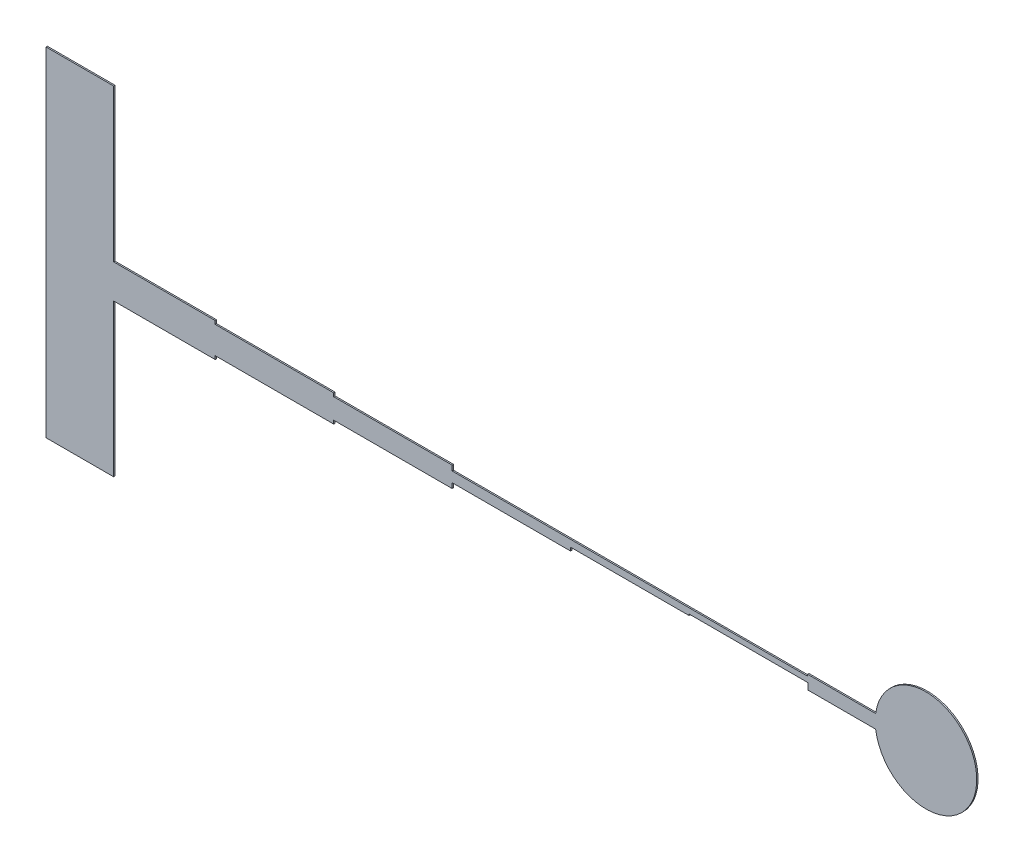
SolidWorks part; units mm, degrees
ref_plane "Front Plane" through (0, 0, 0) normal (0, 0, 1) x (1, 0, 0)
ref_plane "Top Plane" through (0, 0, 0) normal (0, 1, 0) x (1, 0, 0)
ref_plane "Right Plane" through (0, 0, 0) normal (1, 0, 0) x (0, 0, -1)
sketch "Sketch1" plane through (0, 0, 0) normal (0, 0, 1) x (1, 0, 0)
  line L0 (1000, 250) -> (5000, 250)
  line L1 (-1000, 2500) -> (1000, 2500)
  line L2 (-1000, 2500) -> (-1000, -2500)
  line L3 (-1000, -2500) -> (1000, -2500)
  line L4 (1000, 2500) -> (1000, 250)
  line L5 (-1000, 2500) -> (1000, -2500) construction
  line L6 (-1000, -2500) -> (1000, 2500) construction
  line L9 (1000, -250) -> (5000, -250)
  line L10 (5000, 250) -> (5000, 125)
  line L11 (-3000, 250) -> (5000, -250) construction
  line L12 (-3000, -250) -> (5000, 250) construction
  line L13 (5000, 125) -> (9000, 125)
  line L15 (5000, -125) -> (9000, -125)
  line L16 (9000, 125) -> (9000, 100)
  line L17 (1000, 125) -> (9000, -125) construction
  line L18 (1000, -125) -> (9000, 125) construction
  line L19 (9000, 100) -> (11256.6966, 100)
  line L21 (9000, -100) -> (11256.6966, -100)
  line L23 (6000, 100) -> (12000, -100) construction
  line L24 (6000, -100) -> (12000, 100) construction
  line L25 (1000, -250) -> (1000, -2500)
  line L26 (5000, -125) -> (5000, -250)
  line L27 (9000, -100) -> (9000, -125)
  arc A0 (11256.6966, -100) -> (11256.6966, 100) centre (12000, 0) ccw
  point P0 (0, 0)
  point P6 (1000, 0)
  point P11 (5000, 0)
  point P16 (9000, 0)
  dimension "D9" = 1500
  dimension "D1" = 2000
  dimension "D2" = 5000
  dimension "D3" = 500
  dimension "D4" = 4000
  dimension "D5" = 250
  dimension "D6" = 4000
  dimension "D7" = 200
extrude "Boss-Extrude1" add sketch "Sketch1" against normal blind 20
sketch "Sketch2" plane through (0, 0, 0) normal (0, 0, 1) x (1, 0, 0)
  line L0 (0, -11) -> (0, 11) construction
  line L1 (1000, 2500) -> (0, 2500)
  line L2 (1000, 2500) -> (1000, 250)
  line L3 (1000, 250) -> (0, 250)
  line L4 (0, 2500) -> (0, 250)
  line L5 (1000, -2500) -> (0, -2500)
  line L6 (1000, -2500) -> (1000, -250)
  line L7 (1000, -250) -> (0, -250)
  line L8 (0, -2500) -> (0, -250)
  dimension "D1" = 1000
  dimension "D2" = 2250
extrude "Cut-Extrude1" cut sketch "Sketch2" against normal through all
sketch "Sketch3" plane through (0, 0, 0) normal (0, 0, 1) x (1, 0, 0)
  line L0 (0, 0) -> (1098.3807, 0) construction
  line L1 (11, 0) -> (-11, 0) construction
  line L2 (5000, 250) -> (0, 250) construction
  line L3 (1500, 250) -> (3250, 250)
  line L4 (1500, 250) -> (1500, 200)
  line L5 (1500, 200) -> (3250, 200)
  line L7 (0, -250) -> (5000, -250) construction
  line L8 (1500, -250) -> (3250, -250)
  line L9 (1500, -250) -> (1500, -200)
  line L10 (1500, -200) -> (3250, -200)
  line L12 (0, -11) -> (0, 11) construction
  line L13 (3250, 200) -> (3250, 150)
  line L14 (3250, 250) -> (5000, 250)
  line L16 (3250, 150) -> (5000, 150)
  line L17 (5000, 250) -> (5000, 150)
  line L18 (3250, -250) -> (5000, -250)
  line L19 (3250, -200) -> (3250, -150)
  line L20 (3250, -150) -> (5000, -150)
  line L21 (5000, -250) -> (5000, -150)
  point P17 (1500, 225)
  dimension "D1" = 1098.3807
  dimension "D2" = 1750
  dimension "D3" = 50
  dimension "D4" = 1750
  dimension "D5" = 50
  dimension "D6" = 1500
  dimension "D7" = 1500
  dimension "D8" = 100
  dimension "D9" = 100
  dimension "D10" = 1750
  dimension "D11" = 1750
extrude "Cut-Extrude4" cut sketch "Sketch3" against normal through all contours L8 L18 L21 L20 L19 L10 L9
mirror "Mirror1" about plane through (0, 0, 0) normal (0, 1, 0) of "Cut-Extrude4"
sketch "Sketch4" plane through (0, 0, 0) normal (0, 0, 1) x (1, 0, 0)
  line L1 (5000, 125) -> (6750, 125)
  line L2 (5000, 125) -> (5000, 75)
  line L3 (5000, 75) -> (6750, 75)
  line L4 (6750, 125) -> (6750, 75)
  dimension "D1" = 1750
  dimension "D2" = 50
extrude "Cut-Extrude5" cut sketch "Sketch4" against normal through all
mirror "Mirror2" about plane through (0, 0, 0) normal (0, 1, 0) of "Cut-Extrude5"
sketch "Sketch5" plane through (0, 0, 0) normal (0, 0, 1) x (1, 0, 0)
  line L1 (6750, 125) -> (8500, 125)
  line L2 (6750, 125) -> (6750, 75)
  line L3 (6750, 75) -> (8500, 75)
  line L4 (8500, 125) -> (8500, 75)
  dimension "D1" = 1750
  dimension "D2" = 50
extrude "Cut-Extrude6" cut sketch "Sketch5" against normal through all
sketch "Sketch6" plane through (0, 0, 0) normal (0, 0, 1) x (1, 0, 0)
  line L1 (8500, 125) -> (10250, 125)
  line L2 (8500, 125) -> (8500, 75)
  line L3 (8500, 75) -> (10250, 75)
  line L4 (10250, 125) -> (10250, 75)
  line L5 (11, 0) -> (-11, 0) construction
  dimension "D1" = 1750
  dimension "D2" = 50
  dimension "D3" = 75
sketch "Sketch8" plane through (0, 0, 0) normal (0, 0, 1) x (1, 0, 0)
  line L1 (6750, -125) -> (8500, -125)
  line L2 (6750, -125) -> (6750, -25)
  line L3 (6750, -25) -> (8500, -25)
  line L4 (8500, -125) -> (8500, -25)
  dimension "D1" = 100
  dimension "D2" = 1750
extrude "Cut-Extrude7" cut sketch "Sketch8" against normal through all
extrude "Cut-Extrude8" cut sketch "Sketch6" against normal through all
sketch "Sketch9" plane through (0, 0, 0) normal (0, 0, 1) x (1, 0, 0)
  line L0 (8500, -25) -> (6750, -25) construction
  line L1 (8500, -125) -> (10259.9128, -125)
  line L2 (8500, -125) -> (8500, -5)
  line L3 (8500, -5) -> (10259.9128, -5)
  line L4 (10259.9128, -125) -> (10259.9128, -5)
  dimension "D1" = 20
extrude "Cut-Extrude9" cut sketch "Sketch9" against normal through all
